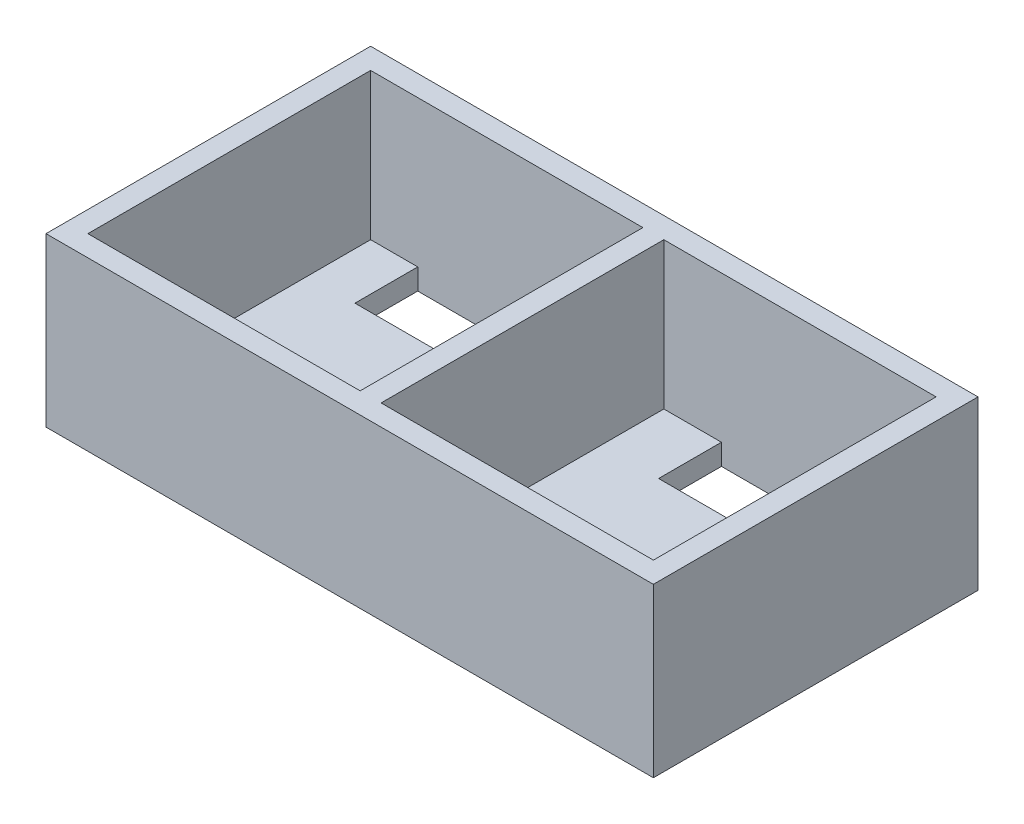
SolidWorks part; units mm, degrees
ref_plane "Front Plane" through (0, 0, 0) normal (0, 0, 1) x (1, 0, 0)
ref_plane "Top Plane" through (0, 0, 0) normal (0, 1, 0) x (1, 0, 0)
ref_plane "Right Plane" through (0, 0, 0) normal (1, 0, 0) x (0, 0, -1)
sketch "Sketch1" plane through (0, 0, 0) normal (0, 1, 0) x (1, 0, 0)
  line L0 (0, 7.75) -> (0, -7.75) construction
  line L1 (-14.5, -7.75) -> (14.5, -7.75)
  line L2 (-14.5, -7.75) -> (-14.5, 7.75)
  line L3 (-14.5, 7.75) -> (14.5, 7.75)
  line L4 (14.5, -7.75) -> (14.5, 7.75)
  point P6 (0, 0)
  dimension "D1" = 15.5
  dimension "D2" = 29
extrude "Boss-Extrude1" add sketch "Sketch1" along normal blind 8
shell "Shell1" thickness 1
sketch "Sketch2" plane through (0, 1, 0) normal (0, 1, 0) x (1, 0, 0)
  line L0 (0, 0) -> (0, 6.75) construction
  line L1 (13.5, 6.75) -> (-13.5, 6.75) construction
  line L2 (-0.5, 6.75) -> (-0.5, -6.75)
  line L3 (-13.5, -6.75) -> (13.5, -6.75) construction
  line L4 (-0.5, 6.75) -> (0.5, 6.75)
  line L5 (13.5, 6.75) -> (-13.5, 6.75) construction
  line L6 (0.5, 6.75) -> (0.5, -6.75)
  line L7 (-13.5, -6.75) -> (13.5, -6.75) construction
  line L8 (0.5, -6.75) -> (-0.5, -6.75)
  dimension "D1" = 1
  dimension "D2" = 1
extrude "Boss-Extrude2" add sketch "Sketch2" along normal blind 7
sketch "Sketch3" plane through (0, 1, 0) normal (0, 1, 0) x (1, 0, 0)
  line L0 (0, 0) -> (0, 7.75) construction
  line L1 (14.5, 7.75) -> (-14.5, 7.75) construction
  line L2 (0, 0) -> (-14.5, 0) construction
  line L3 (-14.5, 7.75) -> (-14.5, -7.75) construction
  line L4 (-7.25, 0) -> (-7.25, 6.75) construction
  line L5 (-0.5, 6.75) -> (-13.5, 6.75) construction
  line L6 (-3.25, 6.75) -> (-11.25, 6.75)
  line L7 (-3.25, -6.75) -> (-3.25, -3.75)
  line L8 (-11.25, 6.75) -> (-3.25, 6.75)
  line L9 (-11.25, 6.75) -> (-11.25, 3.75)
  line L10 (-11.25, 3.75) -> (-3.25, 3.75)
  line L11 (-3.25, 6.75) -> (-3.25, 3.75)
  line L12 (-11.25, -3.75) -> (-3.25, -3.75)
  line L13 (-11.25, -6.75) -> (-11.25, -3.75)
  line L14 (-11.25, -6.75) -> (-3.25, -6.75)
  line L15 (-3.25, -6.75) -> (-11.25, -6.75)
  line L16 (-3.25, -6.75) -> (-3.25, -3.75)
  line L17 (-11.25, 6.75) -> (-11.25, 3.75)
  line L18 (-3.25, 6.75) -> (-3.25, 3.75)
  line L19 (-11.25, -6.75) -> (-11.25, -3.75)
  line L20 (-3.25, -6.75) -> (-3.25, -3.75)
  line L21 (-11.25, 6.75) -> (-11.25, 3.75)
  line L22 (-3.25, 6.75) -> (-3.25, 3.75)
  line L23 (-11.25, -6.75) -> (-11.25, -3.75)
  line L24 (-3.25, -6.75) -> (-3.25, -3.75)
  line L25 (-11.25, 6.75) -> (-11.25, 3.75)
  line L26 (-3.25, 6.75) -> (-3.25, 3.75)
  line L27 (-11.25, -6.75) -> (-11.25, -3.75)
  line L28 (7.25, 0) -> (7.25, 6.75) construction
  line L29 (11.25, -6.75) -> (11.25, -3.75)
  line L30 (3.25, 6.75) -> (3.25, 3.75)
  line L31 (11.25, 6.75) -> (11.25, 3.75)
  line L32 (3.25, -6.75) -> (3.25, -3.75)
  line L33 (11.25, -6.75) -> (11.25, -3.75)
  line L34 (3.25, 6.75) -> (3.25, 3.75)
  line L35 (11.25, 6.75) -> (11.25, 3.75)
  line L36 (3.25, -6.75) -> (3.25, -3.75)
  line L37 (11.25, -6.75) -> (11.25, -3.75)
  line L38 (3.25, 6.75) -> (3.25, 3.75)
  line L39 (11.25, 6.75) -> (11.25, 3.75)
  line L40 (3.25, -6.75) -> (3.25, -3.75)
  line L41 (3.25, -6.75) -> (11.25, -6.75)
  line L42 (11.25, -6.75) -> (3.25, -6.75)
  line L43 (11.25, -6.75) -> (11.25, -3.75)
  line L44 (11.25, -3.75) -> (3.25, -3.75)
  line L45 (3.25, 6.75) -> (3.25, 3.75)
  line L46 (11.25, 3.75) -> (3.25, 3.75)
  line L47 (11.25, 6.75) -> (11.25, 3.75)
  line L48 (11.25, 6.75) -> (3.25, 6.75)
  line L49 (3.25, -6.75) -> (3.25, -3.75)
  line L50 (3.25, 6.75) -> (11.25, 6.75)
  line L51 (3.25, 6.75) -> (11.25, 6.75)
  point P14 (-7.25, 6.75)
  point P22 (-7.25, -6.75)
  point P33 (7.25, -6.75)
  point P34 (7.25, 6.75)
  line M9 (-0.5, 6.75) -> (-13.5, 6.75)
  line M11 (-13.5, -6.75) -> (-0.5, -6.75)
  dimension "D1" = 3
extrude "Cut-Extrude1" cut sketch "Sketch3" against normal blind 7 contours L11 L9 L10 M9 | L31 L48 L30 L46 | L29 L44 L32 L41 | L13 L7 L12 M11
